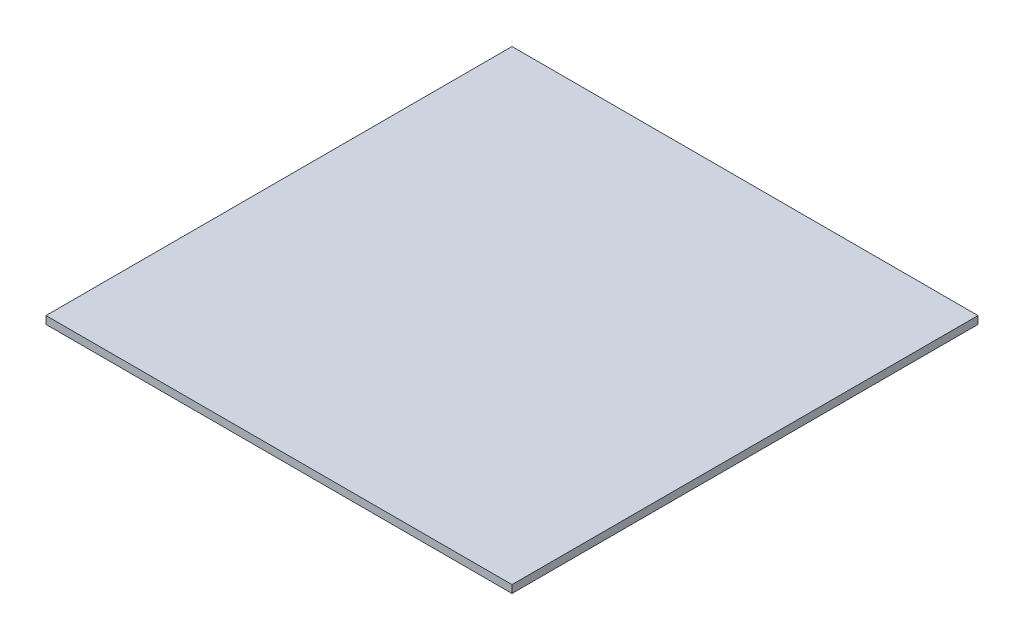
SolidWorks part; units mm, degrees
ref_plane "Front Plane" through (0, 0, 0) normal (0, 0, 1) x (1, 0, 0)
ref_plane "Top Plane" through (0, 0, 0) normal (0, 1, 0) x (1, 0, 0)
ref_plane "Right Plane" through (0, 0, 0) normal (1, 0, 0) x (0, 0, -1)
sketch "Sketch1" plane through (0, 0, 0) normal (0, 1, 0) x (1, 0, 0)
  line L1 (-2.8921, 1.5658) -> (188.8779, 1.5658)
  line L2 (-2.8921, 1.5658) -> (-2.8921, -190.2042)
  line L3 (-2.8921, -190.2042) -> (188.8779, -190.2042)
  line L4 (188.8779, 1.5658) -> (188.8779, -190.2042)
  dimension "D1" = 191.77
  dimension "D2" = 191.77
extrude "Boss-Extrude1" add sketch "Sketch1" along normal blind 3.175
